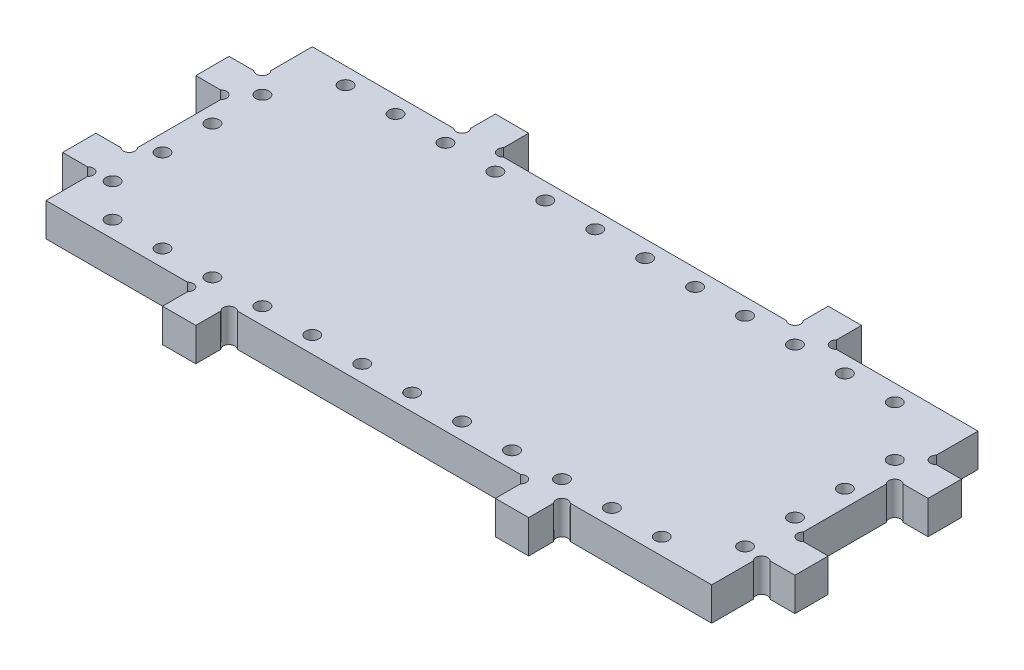
SolidWorks part; units mm, degrees
material "6061 Alloy"
ref_plane "Front" through (0, 0, 0) normal (0, 0, 1) x (1, 0, 0)
ref_plane "Top" through (0, 0, 0) normal (0, 1, 0) x (1, 0, 0)
ref_plane "Right" through (0, 0, 0) normal (1, 0, 0) x (0, 0, -1)
sketch "Sketch2" plane through (0, 0, 0) normal (0, 1, 0) x (1, 0, 0)
  line L1 (-127, -50.8) -> (127, -50.8)
  line L2 (-127, -50.8) -> (-127, 50.8)
  line L3 (-127, 50.8) -> (127, 50.8)
  line L4 (127, -50.8) -> (127, 50.8)
  line L5 (-127, -50.8) -> (127, 50.8) construction
  line L6 (-127, 50.8) -> (127, -50.8) construction
  point P0 (0, 0)
  dimension "D1" = 254
  dimension "D2" = 101.6
extrude "Rectangle Extrusion" add sketch "Sketch2" along normal blind 12.7
sketch "Sketch4" plane through (0, 0, 50.8) normal (0, 0, 1) x (1, 0, 0)
  line L0 (-127, 12.7) -> (-63.5, 12.7) construction
  line L1 (-127, 12.7) -> (127, 12.7) construction
  line L2 (-63.5, 12.7) -> (-63.5, 6.35) construction
  line L3 (-127, 0) -> (127, 0) construction
  line L4 (-57.15, 12.7) -> (-69.85, 12.7)
  line L5 (-57.15, 12.7) -> (-57.15, 0)
  line L6 (-57.15, 0) -> (-69.85, 0)
  line L7 (-69.85, 12.7) -> (-69.85, 0)
  line L8 (-57.15, 12.7) -> (-69.85, 0) construction
  line L9 (-57.15, 0) -> (-69.85, 12.7) construction
  line L10 (0, 12.7) -> (0, 0) construction
  line L11 (57.15, 0) -> (69.85, 0)
  line L12 (69.85, 12.7) -> (69.85, 0)
  line L13 (57.15, 12.7) -> (69.85, 12.7)
  line L14 (57.15, 12.7) -> (57.15, 0)
  dimension "D1" = 63.5
  dimension "D2" = 6.35
  dimension "D3" = 12.7
extrude "Front Face Tabs" add sketch "Sketch4" along normal blind 12.7
mirror "Mirror Rear Face Tabs" about plane through (0, 0, 0) normal (0, 0, 1) of "Front Face Tabs"
sketch "Sketch6" plane through (0, 12.7, 0) normal (0, 1, 0) x (1, 0, 0)
  line L0 (-69.85, 50.8) -> (-127, 50.8) construction
  line L1 (-69.85, 63.5) -> (-69.85, 50.8) construction
  line L2 (-63.5, 63.5) -> (-63.5, 50.1421) construction
  line L3 (-57.15, 63.5) -> (-69.85, 63.5) construction
  line L4 (0, -6.985) -> (0, 6.985) construction
  line L5 (-6.985, 0) -> (6.985, 0) construction
  circle A0 centre (-71.4375, 52.3875) radius 2.2454
  circle A1 centre (-55.5625, 52.3875) radius 2.2454
  circle A2 centre (55.5625, 52.3875) radius 2.2454
  circle A3 centre (71.4375, 52.3875) radius 2.2454
  circle A4 centre (71.4375, -52.3875) radius 2.2454
  circle A5 centre (55.5625, -52.3875) radius 2.2454
  circle A6 centre (-55.5625, -52.3875) radius 2.2454
  circle A7 centre (-71.4375, -52.3875) radius 2.2454
  dimension "D1" = 1.5875
  dimension "D3" = 4.4907
  dimension "D2" = 1.5875
extrude "Tab Curve Front Back" cut sketch "Sketch6" against normal up to surface (12.7 mm away) up to face at (0, 0, 0)
sketch "Sketch7" plane through (127, 0, 0) normal (1, 0, 0) x (0, 0, -1)
  line L0 (-50.8, 12.7) -> (-25.4, 12.7) construction
  line L1 (-50.8, 12.7) -> (50.8, 12.7) construction
  line L2 (-25.4, 12.7) -> (-25.4, 0) construction
  line L3 (69.85, 0) -> (-69.85, 0) construction
  line L4 (0, 6.985) -> (0, -6.985) construction
  line L5 (-31.75, 12.7) -> (-19.05, 12.7)
  line L6 (-31.75, 12.7) -> (-31.75, 0)
  line L7 (-31.75, 0) -> (-19.05, 0)
  line L8 (-19.05, 12.7) -> (-19.05, 0)
  line L9 (-31.75, 12.7) -> (-19.05, 0) construction
  line L10 (-31.75, 0) -> (-19.05, 12.7) construction
  line L11 (31.75, 0) -> (19.05, 0)
  line L12 (19.05, 12.7) -> (19.05, 0)
  line L13 (31.75, 12.7) -> (19.05, 12.7)
  line L14 (31.75, 12.7) -> (31.75, 0)
  point P5 (-25.4, 6.35)
  dimension "D1" = 25.4
  dimension "D2" = 12.7
extrude "Right Face Tabs" add sketch "Sketch7" along normal blind 12.7
mirror "Mirror Left Face Tabs" about plane through (0, 0, 0) normal (1, 0, 0) of "Right Face Tabs"
sketch "Sketch8" plane through (0, 12.7, 0) normal (0, 1, 0) x (1, 0, 0)
  line L0 (139.7, 31.75) -> (127, 31.75) construction
  line L1 (127, 31.75) -> (127, 50.8) construction
  line L2 (139.7, 25.4) -> (126.2032, 25.4) construction
  line L3 (139.7, 31.75) -> (139.7, 19.05) construction
  line L4 (-6.985, 0) -> (6.985, 0) construction
  line L5 (0, -6.985) -> (0, 6.985) construction
  circle A0 centre (128.5875, 33.3375) radius 2.2454
  circle A1 centre (128.5875, 17.4625) radius 2.2454
  circle A2 centre (128.5875, -17.4625) radius 2.2454
  circle A3 centre (128.5875, -33.3375) radius 2.2454
  circle A4 centre (-128.5875, -33.3375) radius 2.2454
  circle A5 centre (-128.5875, -17.4625) radius 2.2454
  circle A6 centre (-128.5875, 17.4625) radius 2.2454
  circle A7 centre (-128.5875, 33.3375) radius 2.2454
  dimension "D3" = 4.4907
  dimension "D1" = 1.5875
  dimension "D2" = 1.5875
extrude "Tab Curve Left Right" cut sketch "Sketch8" against normal up to surface (12.7 mm away) up to face at (0, 0, 0)
sketch "Sketch9" plane through (0, 0, 0) normal (0, -1, 0) x (1, 0, 0)
  circle A0 centre (-107.95, 44.45) radius 2.5527
  circle A1 centre (-120.65, 31.75) radius 2.5527
  circle A2 centre (-120.65, 12.7) radius 2.5527
  circle A3 centre (-120.65, -6.35) radius 2.5527
  circle A4 centre (-120.65, -25.4) radius 2.5527
  circle A5 centre (-88.9, 44.45) radius 2.5527
  circle A6 centre (-69.85, 44.45) radius 2.5527
  circle A7 centre (-50.8, 44.45) radius 2.5527
  circle A8 centre (-31.75, 44.45) radius 2.5527
  circle A9 centre (-12.7, 44.45) radius 2.5527
  circle A10 centre (6.35, 44.45) radius 2.5527
  circle A11 centre (25.4, 44.45) radius 2.5527
  circle A12 centre (44.45, 44.45) radius 2.5527
  circle A13 centre (63.5, 44.45) radius 2.5527
  circle A14 centre (82.55, 44.45) radius 2.5527
  circle A15 centre (101.6, 44.45) radius 2.5527
  circle A16 centre (101.6, -44.45) radius 2.5527
  circle A17 centre (82.55, -44.45) radius 2.5527
  circle A18 centre (63.5, -44.45) radius 2.5527
  circle A19 centre (44.45, -44.45) radius 2.5527
  circle A20 centre (25.4, -44.45) radius 2.5527
  circle A21 centre (6.35, -44.45) radius 2.5527
  circle A22 centre (-12.7, -44.45) radius 2.5527
  circle A23 centre (-31.75, -44.45) radius 2.5527
  circle A24 centre (-50.8, -44.45) radius 2.5527
  circle A25 centre (-69.85, -44.45) radius 2.5527
  circle A26 centre (-88.9, -44.45) radius 2.5527
  circle A27 centre (-107.95, -44.45) radius 2.5527
  circle A28 centre (120.65, -25.4) radius 2.5527
  circle A29 centre (120.65, -6.35) radius 2.5527
  circle A30 centre (120.65, 12.7) radius 2.5527
  circle A31 centre (120.65, 31.75) radius 2.5527
  point P64 (-127, 50.8)
extrude "Cut-Extrude1" cut sketch "Sketch9" against normal through all
